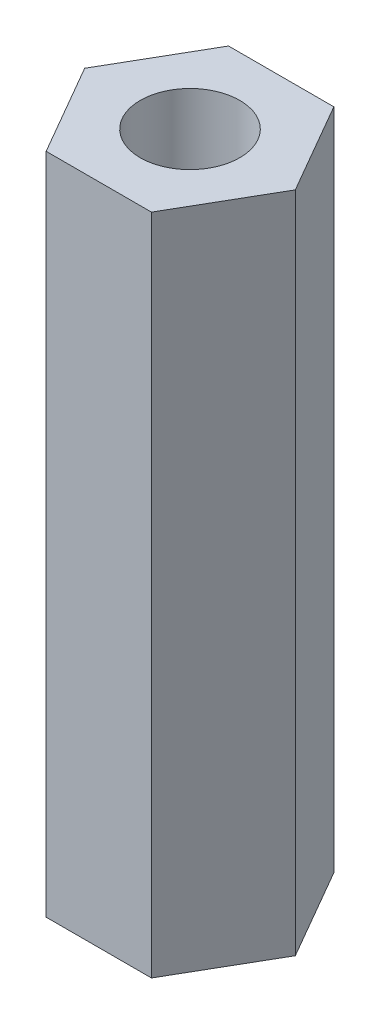
SolidWorks part; units mm, degrees
ref_plane "Front Plane" through (0, 0, 0) normal (0, 0, 1) x (1, 0, 0)
ref_plane "Top Plane" through (0, 0, 0) normal (0, 1, 0) x (1, 0, 0)
ref_plane "Right Plane" through (0, 0, 0) normal (1, 0, 0) x (0, 0, -1)
sketch "Sketch1" plane through (0, 0, 0) normal (0, 1, 0) x (1, 0, 0)
  line L1 (3.1754, 0) -> (1.5877, 2.75)
  line L2 (1.5877, 2.75) -> (-1.5877, 2.75)
  line L3 (-1.5877, 2.75) -> (-3.1754, 0)
  line L4 (-3.1754, 0) -> (-1.5877, -2.75)
  line L5 (-1.5877, -2.75) -> (1.5877, -2.75)
  line L6 (1.5877, -2.75) -> (3.1754, 0)
  circle A0 centre (0, 0) radius 2.75 construction
  dimension "D1" = 5.5
extrude "Boss-Extrude1" add sketch "Sketch1" along normal blind 20
sketch "Sketch2" plane through (0, 20, 0) normal (0, 1, 0) x (1, 0, 0)
  circle A0 centre (0, 0) radius 1.5
  dimension "D1" = 3
extrude "Cut-Extrude1" cut sketch "Sketch2" against normal blind 10
ref_plane "Plane1" through (0, 10, 0) normal (0, -1, 0) x (-1, 0, 0)
mirror "Mirror1" about plane through (0, 10, 0) normal (0, -1, 0) of "Cut-Extrude1"
